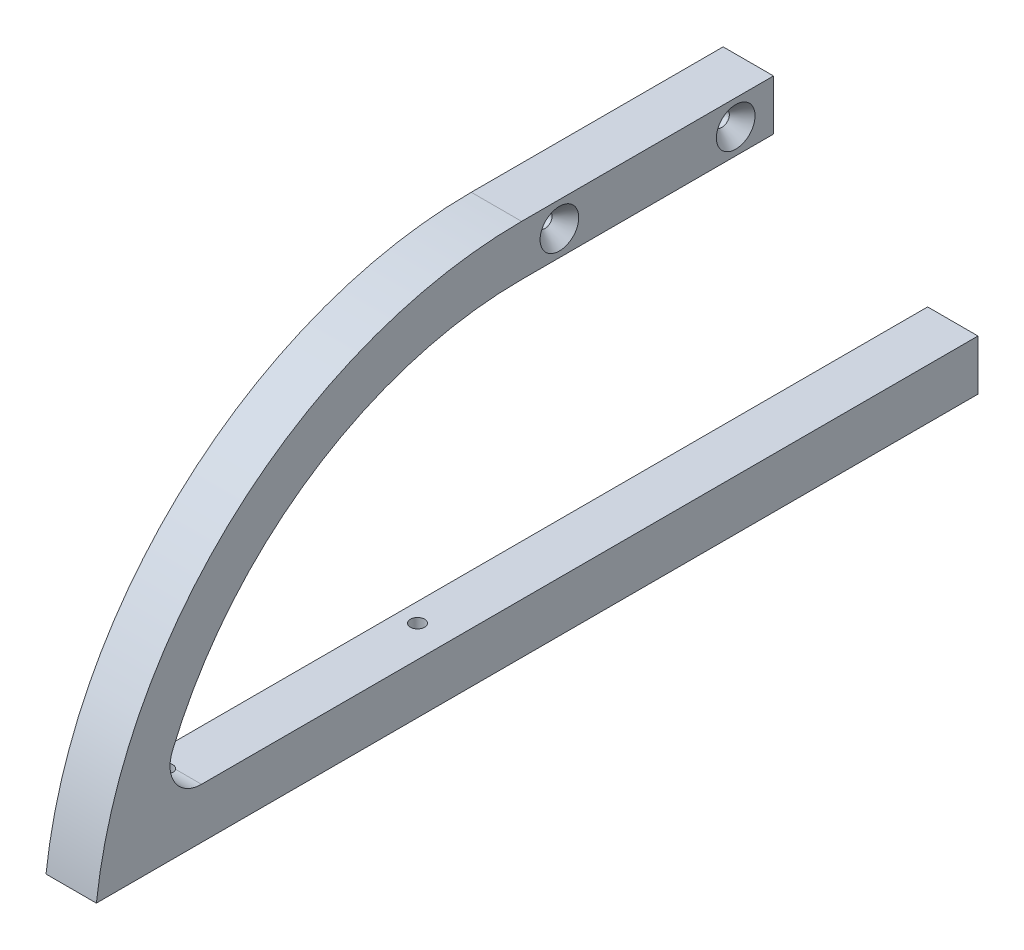
SolidWorks part; units mm, degrees
material "1060 Alloy"
ref_plane "Front Plane" through (0, 0, 0) normal (0, 0, 1) x (1, 0, 0)
ref_plane "Top Plane" through (0, 0, 0) normal (0, 1, 0) x (1, 0, 0)
ref_plane "Right Plane" through (0, 0, 0) normal (1, 0, 0) x (0, 0, -1)
sketch "Sketch1" plane through (0, 0, 0) normal (1, 0, 0) x (0, 0, -1)
  line L0 (-136.5603, -76.2) -> (41.2397, -76.2)
  line L1 (0, 0) -> (-50.8, 0)
  line L2 (0, 0) -> (0, -10.16)
  line L3 (0, -10.16) -> (-50.8, -10.16)
  line L5 (-115.358, -66.04) -> (41.2397, -66.04)
  line L6 (41.2397, -66.04) -> (41.2397, -76.2)
  line L7 (-25.4, 0) -> (-25.4, -10.16) construction
  arc A0 (-50.8, 0) -> (-136.5603, -76.2) centre (-50.8, -86.36) ccw
  arc A1 (-50.8, -10.16) -> (-121.2269, -57.2655) centre (-50.8, -86.36) ccw
  arc A2 (-115.358, -66.04) -> (-121.2269, -57.2655) centre (-115.358, -59.69) cw
  dimension "D1" = 10.16
  dimension "D5" = 76.2
  dimension "D7" = 6.35
  dimension "D2" = 50.8
  dimension "D3" = 177.8
  dimension "D4" = 10.16
  dimension "D6" = 76.2
extrude "Boss-Extrude1" add sketch "Sketch1" along normal blind 10.16
sketch "Sketch2" plane through (10.16, 0, 0) normal (1, 0, 0) x (0, 0, -1)
  line L0 (0, 0) -> (-50.8, 0) construction
  line L2 (0, -10.16) -> (0, 0) construction
  circle A0 centre (-7.62, -5.08) radius 1.4859
  dimension "D1" = 2.9718
  dimension "D2" = 5.08
  dimension "D3" = 7.62
extrude "Cut-Extrude2" cut sketch "Sketch2" against normal through all
sketch "Sketch3" plane through (0, -76.2, 0) normal (0, -1, 0) x (1, 0, 0)
  line L0 (10.16, 136.5603) -> (10.16, -41.2397) construction
  line L1 (10.16, 136.5603) -> (0, 136.5603) construction
  circle A0 centre (3.81, 116.2403) radius 1.4224
  circle A1 centre (3.81, 65.4403) radius 1.4224
  dimension "D1" = 6.35
  dimension "D2" = 2.8448
  dimension "D4" = 2.8448
  dimension "D3" = 20.32
  dimension "D5" = 6.35
  dimension "D6" = 50.8
extrude "Cut-Extrude3" cut sketch "Sketch3" against normal up to next
hole_wizard "CSK for #3 Flat Head Machine Screw (100)1" positions "Sketch4" profile "Sketch5" countersink size "#3" standard "ANSI Inch" end condition through all
sketch "Sketch4" plane through (10.16, 0, 0) normal (1, 0, 0) x (0, 0, -1)
  point P0 (-7.62, -5.08)
sketch "Sketch5" plane through (10.16, -5.08, 7.62) normal (0, 1, 0) x (0, 0, -1)
  line L0 (0, 0) -> (0, 10.16)
  line L1 (0, 10.16) -> (1.397, 10.16)
  line L2 (1.397, 10.16) -> (1.397, 2.8781)
  line L3 (1.397, 2.8781) -> (3.8989, 0)
  line L5 (3.8989, 0) -> (0, 0)
  line L6 (-1.397, 2.8781) -> (-3.8989, 0) construction
  line L11 (0, -6.35) -> (0, 107.95) construction
  dimension "Thru Hole Dia." = 2.794
  dimension "Thru Hole Depth" = 10.16
  dimension "Near C'Sink Dia." = 7.7978
  dimension "Near C'Sink Angle" = 82
ref_plane "Plane1" through (0, 0, 25.4) normal (0, 0, -1) x (-1, 0, 0)
mirror "Mirror1" about plane through (0, 0, 25.4) normal (0, 0, -1) of "CSK for #3 Flat Head Machine Screw (100)1"
